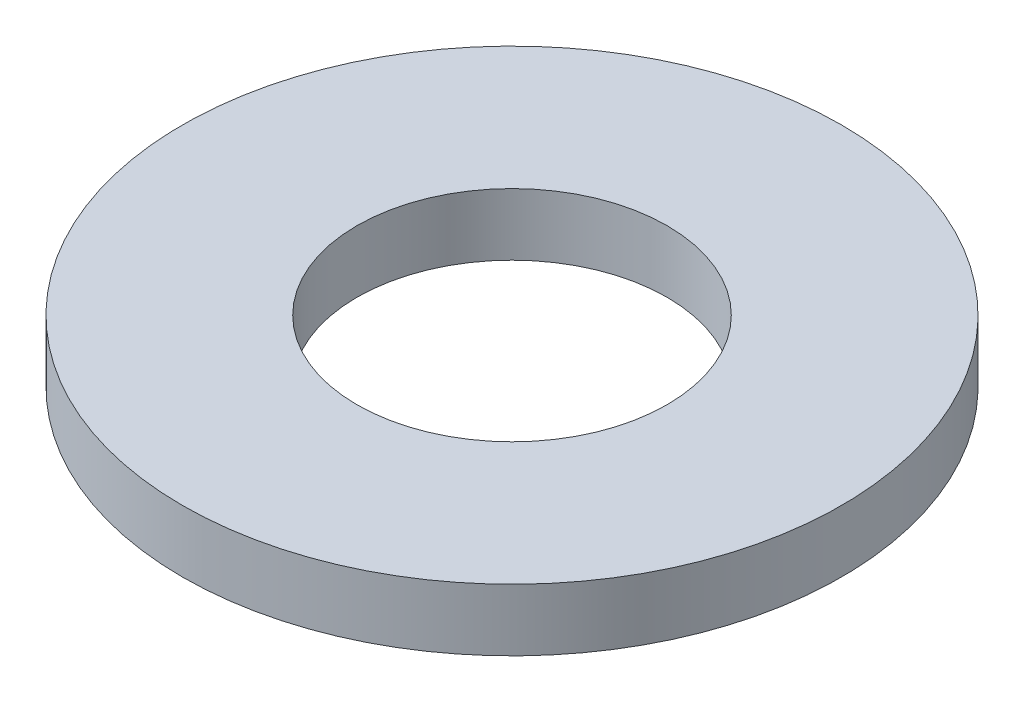
SolidWorks part; units mm, degrees
ref_plane "Front Plane" through (0, 0, 0) normal (0, 0, 1) x (1, 0, 0)
ref_plane "Top Plane" through (0, 0, 0) normal (0, 1, 0) x (1, 0, 0)
ref_plane "Right Plane" through (0, 0, 0) normal (1, 0, 0) x (0, 0, -1)
sketch "Sketch1" plane through (0, 0, 0) normal (0, 1, 0) x (1, 0, 0)
  circle A0 centre (0, 0) radius 1.6
  circle A1 centre (0, 0) radius 3.4
  dimension "D1" = 3.2
  dimension "D2" = 6.8
extrude "Boss-Extrude1" add sketch "Sketch1" along normal blind 0.64
